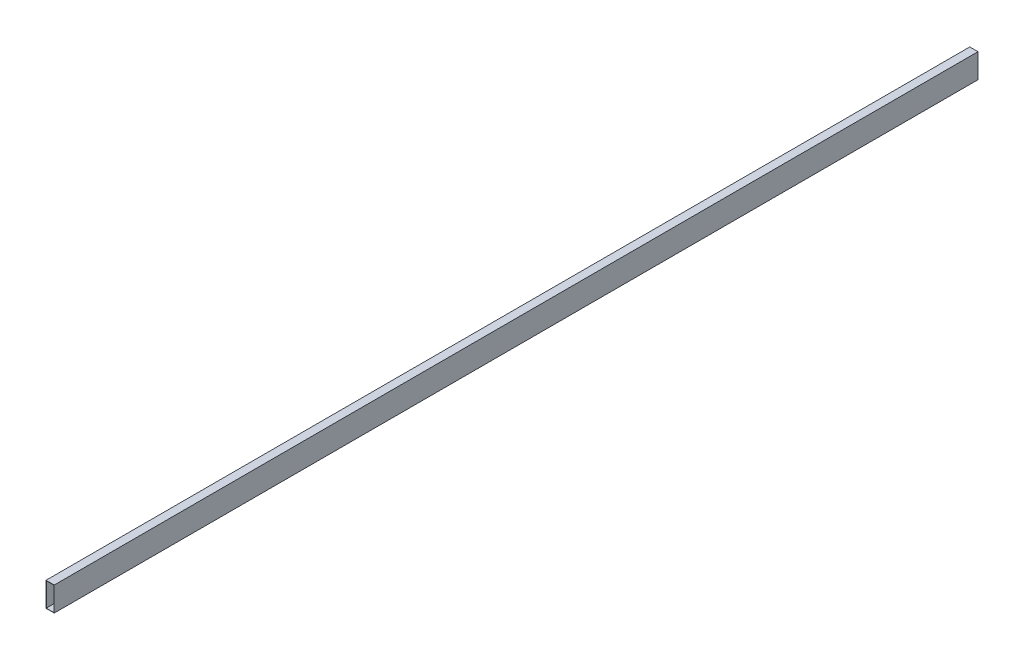
SolidWorks part; units mm, degrees
ref_plane "Front Plane" through (0, 0, 0) normal (0, 0, 1) x (1, 0, 0)
ref_plane "Top Plane" through (0, 0, 0) normal (0, 1, 0) x (1, 0, 0)
ref_plane "Right Plane" through (0, 0, 0) normal (1, 0, 0) x (0, 0, -1)
sketch "Sketch1" plane through (0, 0, 0) normal (0, 0, 1) x (1, 0, 0)
  line L0 (6528.5245, 4657.287) -> (6528.5245, 4617.1823)
  line L1 (6528.969, 4656.8425) -> (6528.969, 4617.6268)
  line L2 (6541.669, 4656.8425) -> (6541.669, 4617.6268)
  line L3 (6542.1135, 4657.287) -> (6528.5245, 4657.287)
  line L4 (6541.669, 4656.8425) -> (6528.969, 4656.8425)
  line L5 (6542.1135, 4657.287) -> (6542.1135, 4617.1823)
  line L6 (6542.1135, 4617.1823) -> (6528.5245, 4617.1823)
  line L7 (6541.669, 4617.6268) -> (6528.969, 4617.6268)
extrude "Boss-Extrude1" add sketch "Sketch1" along normal blind 1524
